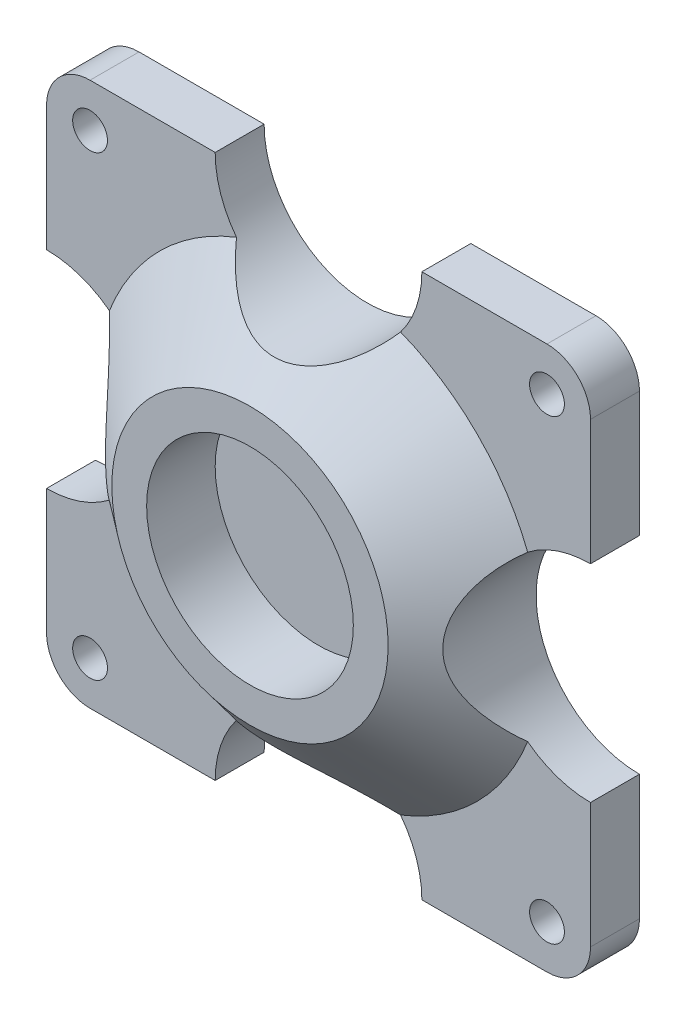
SolidWorks part; units mm, degrees
material "AISI 1035 Steel (SS)"
ref_plane "Front Plane" through (0, 0, 0) normal (0, 0, 1) x (1, 0, 0)
ref_plane "Top Plane" through (0, 0, 0) normal (0, 1, 0) x (1, 0, 0)
ref_plane "Right Plane" through (0, 0, 0) normal (1, 0, 0) x (0, 0, -1)
sketch "Sketch1" plane through (0, 0, 0) normal (0, 0, 1) x (1, 0, 0)
  line L1 (-42, 50) -> (42, 50)
  line L2 (-50, 42) -> (-50, -42)
  line L3 (-42, -50) -> (42, -50)
  line L4 (50, 42) -> (50, -42)
  line L5 (-50, 50) -> (50, -50) construction
  line L6 (-50, -50) -> (50, 50) construction
  arc A0 (-50, -42) -> (-42, -50) centre (-42, -42) ccw
  arc A1 (42, -50) -> (50, -42) centre (42, -42) ccw
  arc A2 (42, 50) -> (50, 42) centre (42, 42) cw
  arc A3 (-42, 50) -> (-50, 42) centre (-42, 42) ccw
  point P0 (0, 0)
  dimension "D2" = 8
  dimension "D1" = 100
extrude "Boss-Extrude1" add sketch "Sketch1" along normal blind 9
sketch "Sketch2" plane through (0, 0, 9) normal (0, 0, 1) x (1, 0, 0)
  circle A0 centre (0, 0) radius 41.3
  dimension "D1" = 82.6
ref_plane "Plane1" through (0, 0, 21.6) normal (0, 0, 1) x (1, 0, 0)
sketch "Sketch3" plane through (0, 0, 21.6) normal (0, 0, 1) x (1, 0, 0)
  circle A0 centre (0, 0) radius 25.4
  circle A1 centre (0, 0) radius 19
  dimension "D1" = 50.8
  dimension "D2" = 38
loft "Loft1" add profiles "Sketch2" section "Sketch2" section "Sketch3"
sketch "Sketch4" plane through (0, 0, 21.6) normal (0, 0, 1) x (1, 0, 0)
  circle A0 centre (0, 0) radius 19
  dimension "D1" = 38
extrude "Cut-Extrude1" cut sketch "Sketch4" against normal up to surface (12.6 mm away) up to face at (0, 0, 9)
sketch "Sketch5" plane through (0, 0, 9) normal (0, 0, 1) x (1, 0, 0)
  circle A0 centre (-42, 42) radius 3.2
  circle A1 centre (42, 42) radius 3.2
  dimension "D1" = 6.4
extrude "Cut-Extrude2" cut sketch "Sketch5" against normal up to surface (9 mm away) up to face at (0, 0, 0)
mirror "Mirror1" about plane through (0, 0, 0) normal (0, 1, 0) of "Cut-Extrude2"
sketch "Sketch6" plane through (0, 0, 9) normal (0, 0, 1) x (1, 0, 0)
  line L0 (-42, -50) -> (42, -50) construction
  line L1 (-19, -50) -> (19, -50)
  line L3 (11.8801, 0) -> (-11.8801, 0) construction
  line L4 (-19, 50) -> (19, 50)
  arc A0 (-19, -50) -> (19, -50) centre (0, -50) cw
  arc A1 (-19, 50) -> (19, 50) centre (0, 50) ccw
  point P3 (0, -50)
  point P6 (0, -31)
  point P7 (18.1646, -50)
  point P8 (0, 0)
  dimension "D1" = 19
extrude "Cut-Extrude3" cut sketch "Sketch6" against normal through all both and the other way through all
sketch "Sketch8" plane through (0, 0, 9) normal (0, 0, 1) x (1, 0, 0)
  line L0 (50, -42) -> (50, 42) construction
  line L1 (50, 19) -> (50, -19)
  line L2 (19, -50) -> (42, -50) construction
  arc A0 (50, -19) -> (50, 19) centre (50, 0) cw
  point P3 (31, 0)
  point P6 (55.9164, 6.2955)
  point P7 (0, 0)
  point P8 (50, 0)
  point P12 (50, -17.1091)
  point P13 (50, -26.3338)
  point P14 (50, 0)
  dimension "D1" = 19
extrude "Cut-Extrude4" cut sketch "Sketch8" against normal through all both and the other way through all
mirror "Mirror3" about plane through (0, 0, 0) normal (1, 0, 0) of "Cut-Extrude4"
equation "\"ContrustionBaseLength\"= 100"
equation "\"D1@Sketch1\"=\"ContrustionBaseLength\""
